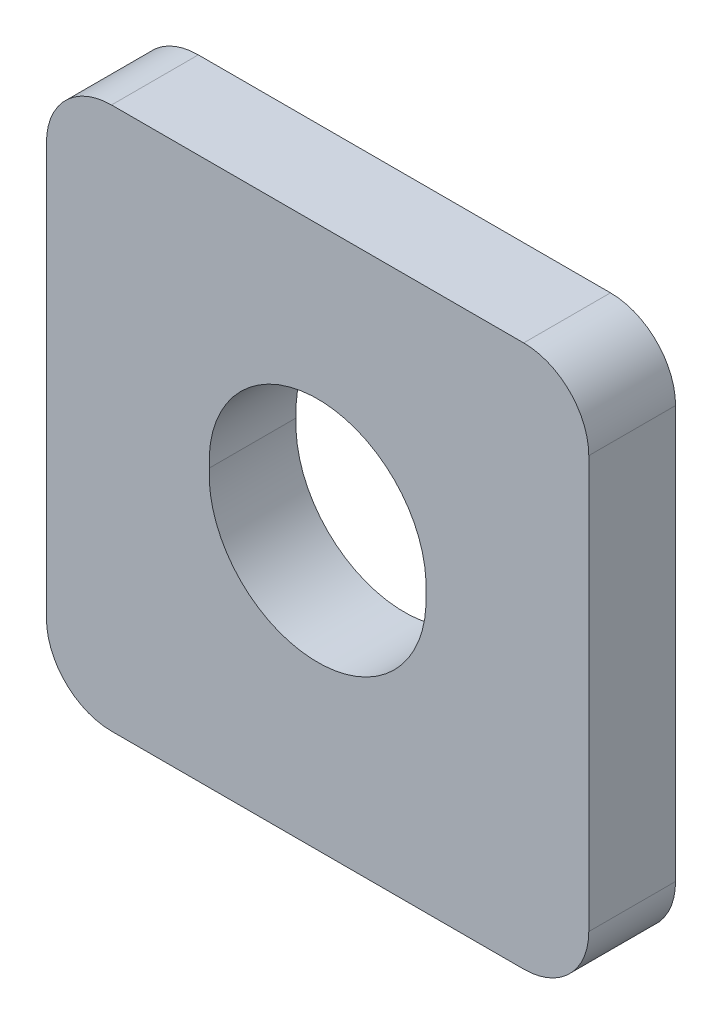
SolidWorks part; units mm, degrees
material "1.0037 (S235JR)"
ref_plane "Plan de face" through (0, 0, 0) normal (0, 0, 1) x (1, 0, 0)
ref_plane "Plan de dessus" through (0, 0, 0) normal (0, 1, 0) x (1, 0, 0)
ref_plane "Plan de droite" through (0, 0, 0) normal (1, 0, 0) x (0, 0, -1)
sketch "Esquisse1" plane through (0, 0, 0) normal (0, 0, 1) x (1, 0, 0)
  line L1 (-9.5, -12.5) -> (9.5, -12.5)
  line L2 (-12.5, -9.5) -> (-12.5, 9.5)
  line L3 (-9.5, 12.5) -> (9.5, 12.5)
  line L4 (12.5, -9.5) -> (12.5, 9.5)
  line L5 (-12.5, -12.5) -> (12.5, 12.5) construction
  line L6 (-12.5, 12.5) -> (12.5, -12.5) construction
  arc A0 (-9.5, -12.5) -> (-12.5, -9.5) centre (-9.5, -9.5) cw
  arc A1 (9.5, -12.5) -> (12.5, -9.5) centre (9.5, -9.5) ccw
  arc A2 (9.5, 12.5) -> (12.5, 9.5) centre (9.5, 9.5) cw
  arc A3 (-12.5, 9.5) -> (-9.5, 12.5) centre (-9.5, 9.5) cw
  circle A4 centre (0, 0) radius 5
  dimension "D3" = 3
  dimension "D4" = 10
  dimension "D1" = 25
  dimension "D2" = 25
extrude "Boss.-Extru.1" add sketch "Esquisse1" along normal blind 4
hole_wizard "Dégagement M82" positions "Esquisse4" profile "Esquisse5" hole size "M8" standard "ISO"
sketch "Esquisse4" plane through (0, -679.4835, 39) normal (0, 0, 1) x (1, 0, 0)
  point P0 (0, 680)
  point P12 (0, 580)
  point P14 (0, 480)
  point P25 (0, 0)
sketch "Esquisse5" plane through (0, 0.5165, 39) normal (1, 0, 0) x (0, -1, 0)
  line L0 (0, 0) -> (0, 225.5043)
  line L1 (0, 225.5043) -> (5, 222.5)
  line L2 (5, 222.5) -> (5, 0)
  line L3 (5, 0) -> (0, 0)
  line L4 (0, 225.5043) -> (-5, 222.5) construction
  line L5 (0, -6.35) -> (0, 107.95) construction
  dimension "Diamètre du perçage" = 10
  dimension "Profondeur du perçage" = 222.5
  dimension "Angle de pointe" = 118
